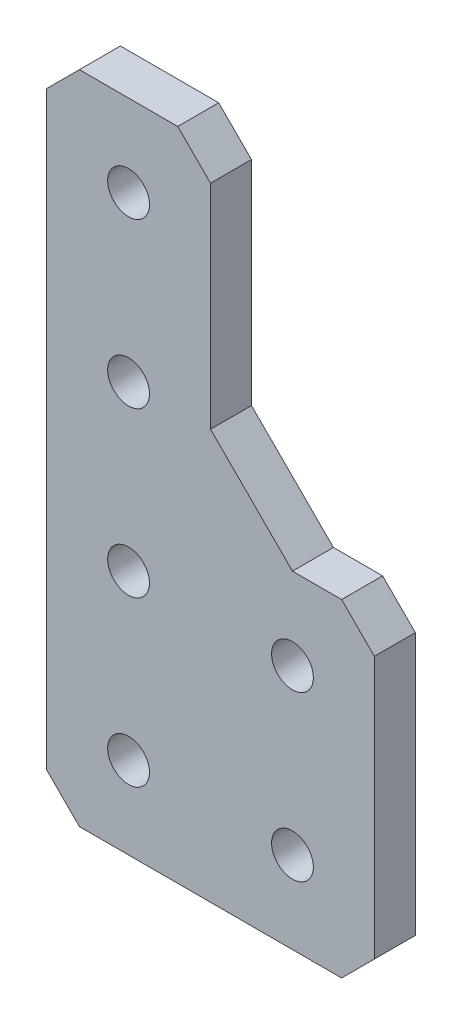
SolidWorks part; units mm, degrees
ref_plane "Front Plane" through (0, 0, 0) normal (0, 0, 1) x (1, 0, 0)
ref_plane "Top Plane" through (0, 0, 0) normal (0, 1, 0) x (1, 0, 0)
ref_plane "Right Plane" through (0, 0, 0) normal (1, 0, 0) x (0, 0, -1)
sketch "Sketch1" plane through (0, 0, 0) normal (0, 0, 1) x (1, 0, 0)
  line L0 (0, 0) -> (0, 80)
  line L1 (0, 80) -> (20, 80)
  line L3 (40, 0) -> (0, 0)
  line L4 (40, 0) -> (40, 40)
  line L5 (40, 40) -> (20, 40)
  line L6 (20, 80) -> (20, 40)
  dimension "D1" = 80
  dimension "D2" = 20
  dimension "D3" = 40
  dimension "D4" = 40
extrude "Boss-Extrude1" add sketch "Sketch1" along normal blind 5
sketch "Sketch2" plane through (0, 0, 5) normal (0, 0, 1) x (1, 0, 0)
  line L0 (10, 80) -> (10, 0) construction
  line L1 (20, 80) -> (0, 80) construction
  line L2 (0, 0) -> (40, 0) construction
  line L3 (0, 70) -> (20, 70) construction
  line L4 (0, 80) -> (0, 0) construction
  line L6 (0, 50) -> (20, 50) construction
  line L7 (0, 10) -> (30, 10) construction
  line L8 (0, 30) -> (30, 30) construction
  line L9 (30, 40) -> (30, 0) construction
  line L10 (40, 40) -> (20, 40) construction
  line L11 (0, 0) -> (40, 0) construction
  line L12 (40, 0) -> (40, 40) construction
  line L13 (20, 40) -> (20, 80) construction
  circle A0 centre (10, 70) radius 2.55
  circle A1 centre (10, 50) radius 2.55
  circle A2 centre (10, 30) radius 2.55
  circle A3 centre (10, 10) radius 2.55
  circle A4 centre (30, 30) radius 2.55
  circle A5 centre (30, 10) radius 2.55
  dimension "D3" = 5.1
  dimension "D4" = 5.1
  dimension "D7" = 5.1
  dimension "D8" = 5.1
  dimension "D10" = 5.1
  dimension "D11" = 5.1
  dimension "D1" = 10
  dimension "D2" = 20
  dimension "D5" = 10
  dimension "D6" = 20
  dimension "D9" = 10
extrude "Cut-Extrude1" cut sketch "Sketch2" against normal blind 10
chamfer "Chamfer1" distance 10 angle 45 1 edges at (20, 40, 2.5)
chamfer "Chamfer2" distance 4 angle 45 1 edges at (20, 80, 2.5)
chamfer "Chamfer3" distance 4 angle 45 4 edges at (0, 80, 2.5) (0, 0, 2.5) (40, 0, 2.5) (40, 40, 2.5)
